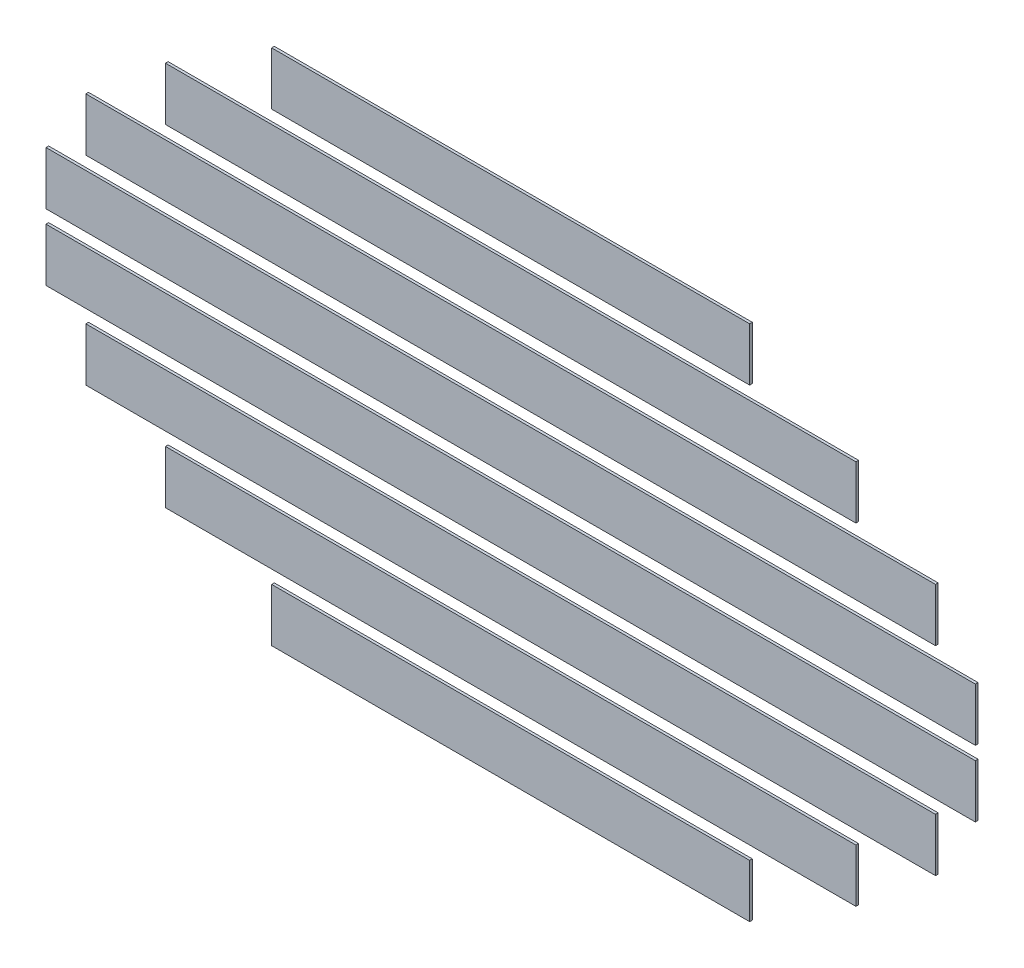
SolidWorks part; units mm, degrees
ref_plane "Plan de face" through (0, 0, 0) normal (0, 0, 1) x (1, 0, 0)
ref_plane "Plan de dessus" through (0, 0, 0) normal (0, 1, 0) x (1, 0, 0)
ref_plane "Plan de droite" through (0, 0, 0) normal (1, 0, 0) x (0, 0, -1)
sketch "Esquisse1" plane through (0, 0, 0) normal (0, 0, 1) x (1, 0, 0)
  line L0 (-11.5668, 98.3946) -> (-11.5668, 3.3946) construction
  line L1 (-186.5668, 23.3946) -> (163.4332, 23.3946)
  line L2 (-186.5668, 23.3946) -> (-186.5668, 3.3946)
  line L3 (-186.5668, 3.3946) -> (163.4332, 3.3946)
  line L4 (-11.5668, 23.3946) -> (-11.5668, 3.3946)
  line L5 (148.4332, 28.3946) -> (-171.5668, 28.3946)
  line L6 (-11.5668, 28.3946) -> (-11.5668, 48.3946)
  line L7 (148.4332, 48.3946) -> (-171.5668, 48.3946)
  line L8 (-171.5668, 28.3946) -> (-171.5668, 48.3946)
  line L9 (118.4332, 53.3946) -> (-141.5668, 53.3946)
  line L10 (-11.5668, 53.3946) -> (-11.5668, 73.3946)
  line L11 (118.4332, 73.3946) -> (-141.5668, 73.3946)
  line L12 (-141.5668, 53.3946) -> (-141.5668, 73.3946)
  line L13 (78.4332, 78.3946) -> (-101.5668, 78.3946)
  line L14 (-11.5668, 78.3946) -> (-11.5668, 98.3946)
  line L15 (78.4332, 98.3946) -> (-101.5668, 98.3946)
  line L16 (-101.5668, 78.3946) -> (-101.5668, 98.3946)
  line L17 (-186.5668, 0.8946) -> (-11.5668, 0.8946) construction
  line L18 (78.4332, 78.3946) -> (78.4332, 98.3946)
  line L19 (118.4332, 53.3946) -> (118.4332, 73.3946)
  line L20 (148.4332, 28.3946) -> (148.4332, 48.3946)
  line L21 (163.4332, 23.3946) -> (163.4332, 3.3946)
  line L22 (-11.5668, -96.6054) -> (-11.5668, -1.6054) construction
  line L23 (163.4332, -21.6054) -> (163.4332, -1.6054)
  line L24 (-11.5668, -21.6054) -> (-11.5668, -1.6054)
  line L25 (-186.5668, -1.6054) -> (163.4332, -1.6054)
  line L26 (-186.5668, -21.6054) -> (-186.5668, -1.6054)
  line L27 (148.4332, -26.6054) -> (148.4332, -46.6054)
  line L28 (118.4332, -51.6054) -> (118.4332, -71.6054)
  line L29 (78.4332, -76.6054) -> (78.4332, -96.6054)
  line L30 (-101.5668, -76.6054) -> (-101.5668, -96.6054)
  line L31 (78.4332, -96.6054) -> (-101.5668, -96.6054)
  line L32 (-11.5668, -76.6054) -> (-11.5668, -96.6054)
  line L33 (78.4332, -76.6054) -> (-101.5668, -76.6054)
  line L34 (-141.5668, -51.6054) -> (-141.5668, -71.6054)
  line L35 (118.4332, -71.6054) -> (-141.5668, -71.6054)
  line L36 (-11.5668, -51.6054) -> (-11.5668, -71.6054)
  line L37 (118.4332, -51.6054) -> (-141.5668, -51.6054)
  line L38 (-171.5668, -26.6054) -> (-171.5668, -46.6054)
  line L39 (148.4332, -46.6054) -> (-171.5668, -46.6054)
  line L40 (-11.5668, -26.6054) -> (-11.5668, -46.6054)
  line L41 (148.4332, -26.6054) -> (-171.5668, -26.6054)
  line L42 (-186.5668, -21.6054) -> (163.4332, -21.6054)
  line L43 (78.4332, -96.6054) -> (-373.8658, -96.6054) construction
  line L44 (-11.5668, 164.2842) -> (-11.5668, -213.5593) construction
  line L45 (-11.5668, 0.8946) -> (449.3718, 0.8946) construction
  line L46 (449.3718, 0.8946) -> (-555.9562, 0.8946) construction
  dimension "D1" = 20
  dimension "D2" = 20
  dimension "D3" = 20
  dimension "D4" = 20
  dimension "D5" = 5
  dimension "D6" = 5
  dimension "D7" = 5
  dimension "D8" = 175
  dimension "D9" = 160
  dimension "D10" = 130
  dimension "D11" = 90
  dimension "D12" = 2.5
extrude "Boss.-Extru.1" add sketch "Esquisse1" along normal blind 1 contours L16 L13 L14 L15 | L13 L18 L15 L14 | L5 L20 L7 L6 | L9 L19 L11 L10 | L8 L5 L6 L7 | L4 L1 L2 L3 | L21 L1 L4 L3 | L24 L42 L23 L25 | L26 L42 L24 L25 | L40 L41 L38 L39 | L27 L41 L40 L39 | L28 L37 L36 L35 | L29 L33 L32 L31 | L32 L33 L30 L31 | L36 L37 L34 L35
